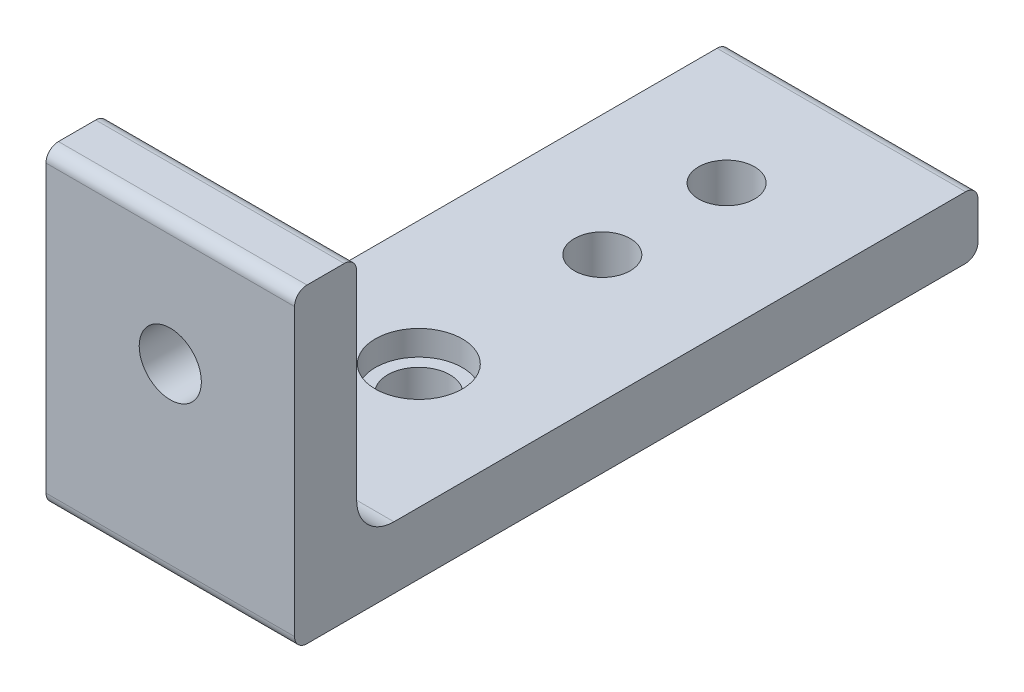
SolidWorks part; units mm, degrees
ref_plane "前视基准面" through (0, 0, 0) normal (0, 0, 1) x (1, 0, 0)
ref_plane "上视基准面" through (0, 0, 0) normal (0, 1, 0) x (1, 0, 0)
ref_plane "右视基准面" through (0, 0, 0) normal (1, 0, 0) x (0, 0, -1)
other "Configuration Table"
sketch "草图1" plane through (0, 0, 0) normal (1, 0, 0) x (0, 0, -1)
  line L0 (0, 0) -> (55, 0)
  line L1 (55, 0) -> (55, 5)
  line L2 (5, 25) -> (0, 25)
  line L3 (0, 25) -> (0, 0)
  line L4 (5, 25) -> (5, 5)
  line L5 (5, 5) -> (55, 5)
  dimension "D1" = 25
  dimension "D2" = 55
  dimension "D3" = 5
  dimension "D4" = 5
extrude "凸台-拉伸1" add sketch "草图1" along normal blind 20
fillet "圆角1" radius 3 1 edges at (10, 5, -5)
fillet "圆角2" radius 1 5 edges at (10, 0, -55) (10, 5, -55) (10, 25, 0) (10, 25, -5) (10, 0, 0)
sketch "草图2" plane through (0, 0, -5) normal (0, 0, -1) x (-1, 0, 0)
  line L0 (-20, 25) -> (0, 25) construction
  line L1 (0, 8) -> (0, 24) construction
  circle A0 centre (-10, 15) radius 2.5
  dimension "D1" = 5
  dimension "D3" = 10
  dimension "D2" = 10
extrude "切除-拉伸1" cut sketch "草图2" against normal blind 20
sketch "草图3" plane through (0, 5, 0) normal (0, 1, 0) x (1, 0, 0)
  line L1 (0, 55) -> (20, 55) construction
  line L2 (0, 54) -> (0, 8) construction
  circle A0 centre (9.7679, 45) radius 2.25
  circle A1 centre (9.7679, 35) radius 2.25
  circle A2 centre (10, 20.0018) radius 2.5
  dimension "D1" = 4.5
  dimension "D2" = 4.5
  dimension "D3" = 5
  dimension "D4" = 10
  dimension "D5" = 10
  dimension "D6" = 15
  dimension "D7" = 10
extrude "切除-拉伸2" cut sketch "草图3" against normal blind 20
sketch "草图5" plane through (0, 5, 0) normal (0, 1, 0) x (1, 0, 0)
  circle A0 centre (10, 20.0018) radius 3.5
extrude "切除-拉伸3" cut sketch "草图5" against normal blind 2
